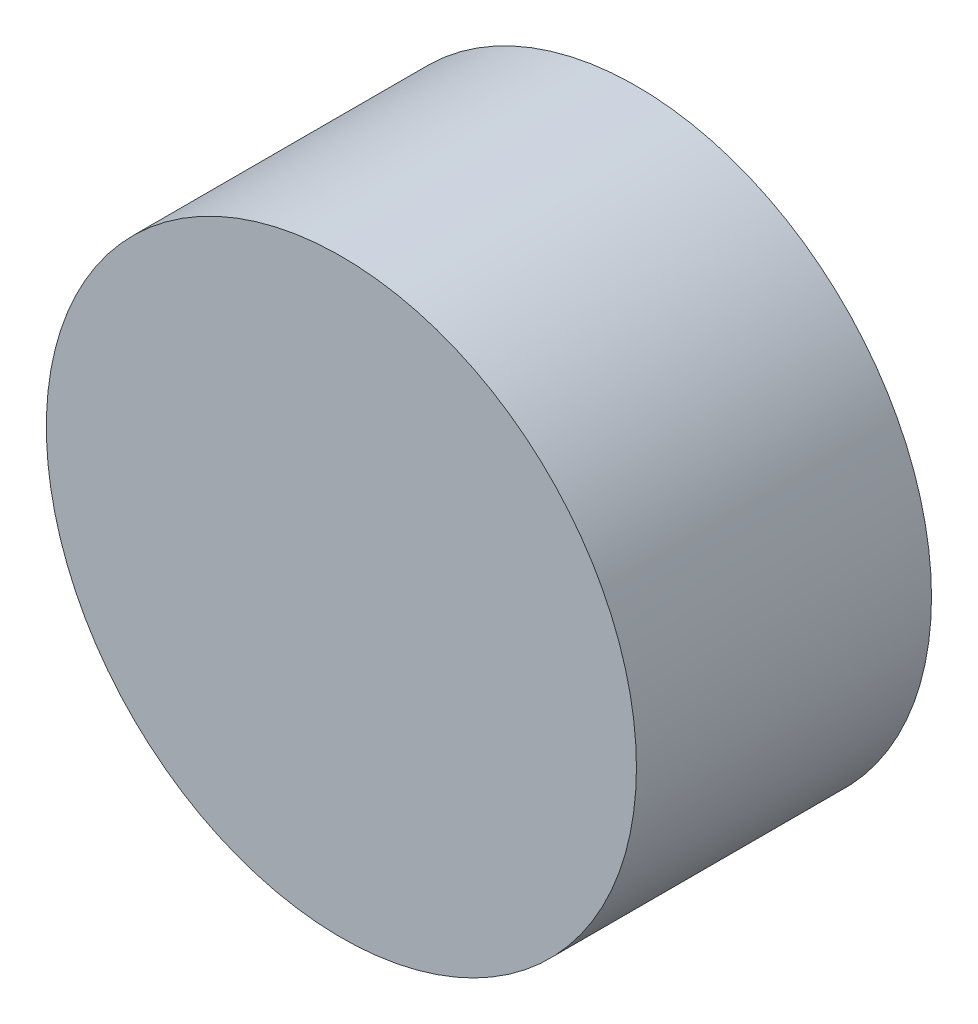
SolidWorks part; units mm, degrees
ref_plane "Front Plane" through (0, 0, 0) normal (0, 0, 1) x (1, 0, 0)
ref_plane "Top Plane" through (0, 0, 0) normal (0, 1, 0) x (1, 0, 0)
ref_plane "Right Plane" through (0, 0, 0) normal (1, 0, 0) x (0, 0, -1)
sketch "Sketch1" plane through (0, 0, 0) normal (0, 0, 1) x (1, 0, 0)
  circle A0 centre (0, 0) radius 15
  dimension "D1" = 30
extrude "Boss-Extrude1" add sketch "Sketch1" along normal blind 15 contours A0
